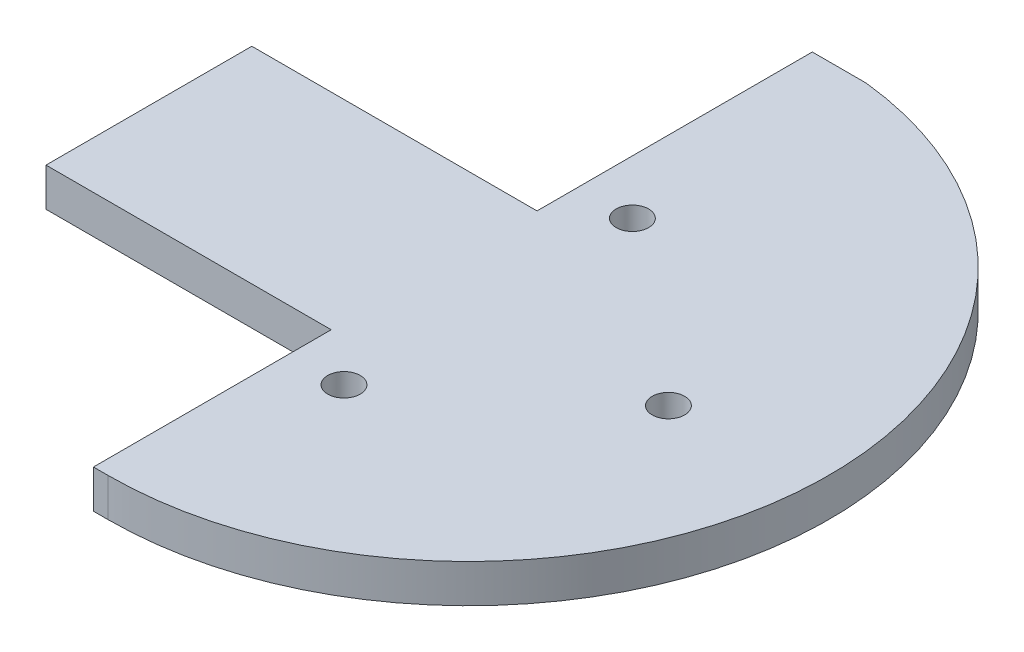
SolidWorks part; units mm, degrees
ref_plane "Front Plane" through (0, 0, 0) normal (0, 0, 1) x (1, 0, 0)
ref_plane "Top Plane" through (0, 0, 0) normal (0, 1, 0) x (1, 0, 0)
ref_plane "Right Plane" through (0, 0, 0) normal (1, 0, 0) x (0, 0, -1)
sketch "Sketch1" plane through (0, 0, 0) normal (0, 1, 0) x (1, 0, 0)
  line L0 (-11.3273, -33.9089) -> (-11.3273, -50.6589)
  line L1 (-31.4213, -19.4071) -> (-11.3273, -19.4071)
  line L2 (-31.4213, -19.4071) -> (-31.4213, -33.9089)
  line L3 (-31.4213, -33.9089) -> (-11.3273, -33.9089)
  line L4 (-31.4213, -26.658) -> (15.0501, -26.658) construction
  line L6 (-7.5173, -16.498) -> (-7.5173, -36.818) construction
  line L8 (-7.5173, -0.013) -> (-11.3273, -0.013)
  line L10 (-10.3113, -50.6589) -> (-11.3273, -50.6589)
  line L11 (-11.3273, -0.013) -> (-11.3273, -19.4071)
  arc A0 (-10.3113, -50.6589) -> (-7.5173, -0.013) centre (-10.3113, -25.2589) ccw
  circle A1 centre (-7.5173, -16.498) radius 1.143
  circle A2 centre (-7.5173, -36.818) radius 1.143
  circle A3 centre (5.1827, -26.658) radius 1.143
  point P15 (-7.5173, -26.658)
  dimension "D3" = 50.8
  dimension "D1" = 2.286
  dimension "D2" = 20.32
  dimension "D4" = 12.7
  dimension "D5" = 3.81
  dimension "D7" = 3.81
extrude "Boss-Extrude1" add sketch "Sketch1" along normal blind 2.7
